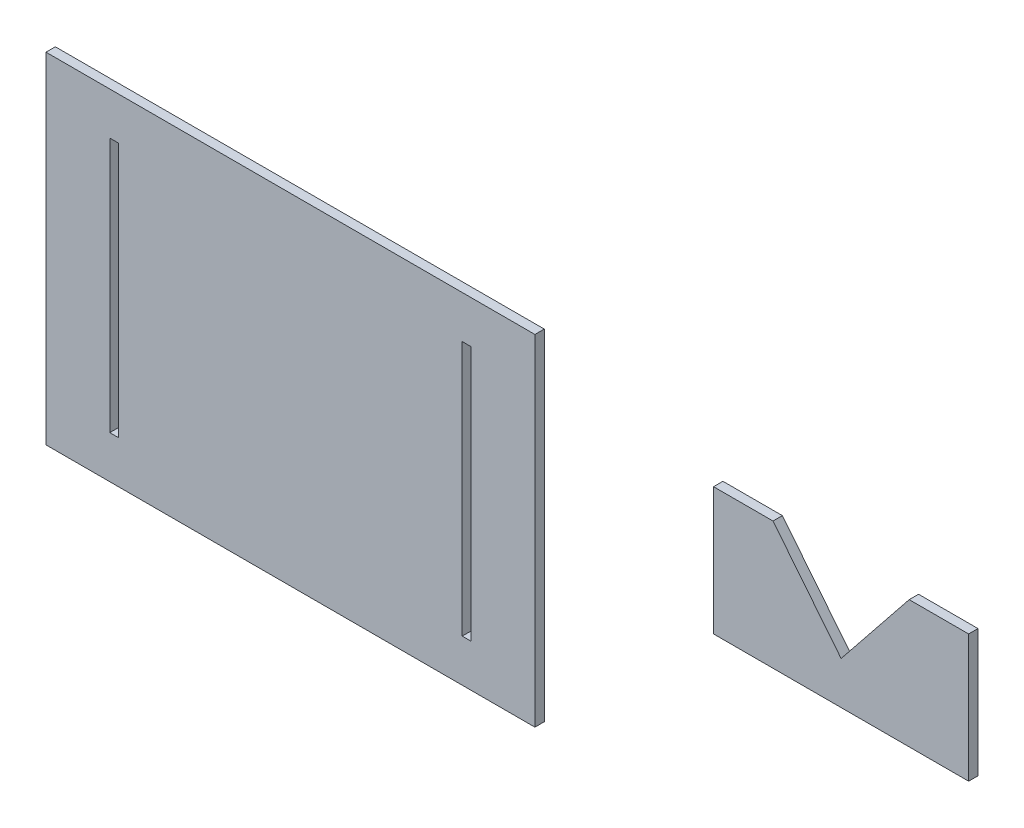
SolidWorks part; units mm, degrees
ref_plane "Front Plane" through (0, 0, 0) normal (0, 0, 1) x (1, 0, 0)
ref_plane "Top Plane" through (0, 0, 0) normal (0, 1, 0) x (1, 0, 0)
ref_plane "Right Plane" through (0, 0, 0) normal (1, 0, 0) x (0, 0, -1)
sketch "Sketch1" plane through (0, 0, 0) normal (0, 0, 1) x (1, 0, 0)
  line L0 (40.4, -30) -> (40.4, -40) construction
  line L1 (-57.5, -40) -> (57.5, -40)
  line L2 (-57.5, -40) -> (-57.5, 40)
  line L3 (-57.5, 40) -> (57.5, 40)
  line L4 (57.5, -40) -> (57.5, 40)
  line L5 (-57.5, -40) -> (57.5, 40) construction
  line L6 (-57.5, 40) -> (57.5, -40) construction
  line L7 (40.4, -30) -> (42.5, -30)
  line L8 (40.4, -30) -> (40.4, 30)
  line L9 (40.4, 30) -> (42.5, 30)
  line L10 (42.5, -30) -> (42.5, 30)
  line L11 (40.4, -30) -> (42.5, 30) construction
  line L12 (40.4, 30) -> (42.5, -30) construction
  line L13 (40.4, 30) -> (40.4, 40) construction
  line L14 (0, 0) -> (0, 22.8958) construction
  line L15 (-40.4, 30) -> (-42.5, -30) construction
  line L16 (-40.4, -30) -> (-42.5, 30) construction
  line L17 (-42.5, -30) -> (-42.5, 30)
  line L18 (-40.4, 30) -> (-42.5, 30)
  line L19 (-40.4, -30) -> (-40.4, 30)
  line L20 (-40.4, -30) -> (-42.5, -30)
  line L21 (113.5057, 30) -> (129.5186, 10)
  line L22 (159.5186, 0) -> (99.5186, 0)
  line L23 (159.5186, 0) -> (159.5186, 30)
  line L24 (159.5186, 30) -> (145.5314, 30)
  line L25 (99.5186, 0) -> (99.5186, 30)
  line L26 (129.5186, 10) -> (145.5314, 30)
  line L27 (113.5057, 30) -> (99.5186, 30)
  line L28 (129.5186, 0) -> (129.5186, 6.293) construction
  circle A0 centre (129.5186, 30) radius 12.5 construction
  point P0 (0, 0)
  point P6 (41.45, 0)
  point P19 (-41.45, 0)
  dimension "D9" = 25
  dimension "D1" = 115
  dimension "D2" = 80
  dimension "D3" = 100
  dimension "D4" = 60
  dimension "D5" = 2.1
  dimension "D6" = 60
  dimension "D7" = 99.5186
  dimension "D8" = 30
  dimension "D10" = 10
extrude "Boss-Extrude1" add sketch "Sketch1" along normal blind 2.2
